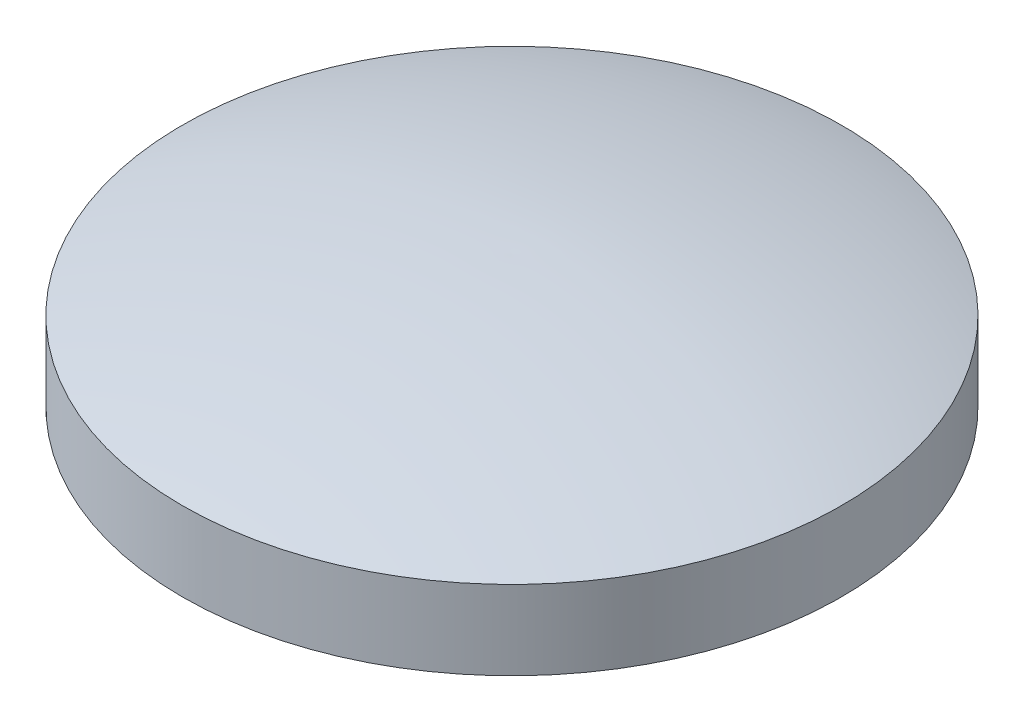
SolidWorks part; units mm, degrees
ref_plane "Front Plane" through (0, 0, 0) normal (0, 0, 1) x (1, 0, 0)
ref_plane "Top Plane" through (0, 0, 0) normal (0, 1, 0) x (1, 0, 0)
ref_plane "Right Plane" through (0, 0, 0) normal (1, 0, 0) x (0, 0, -1)
sketch "Sketch1" plane through (0, 0, 0) normal (0, 1, 0) x (1, 0, 0)
  circle A0 centre (0, 0) radius 12.5
  dimension "D1" = 25
extrude "Boss-Extrude1" add sketch "Sketch1" along normal blind 3
sketch "Sketch2" plane through (0, 0, 0) normal (1, 0, 0) x (0, 0, -1)
  line L0 (0, 3) -> (0, 5.0272)
  line L1 (-12.5, 3) -> (0, 3)
  line L2 (12.5, 3) -> (-12.5, 3) construction
  spline S0 degree 3 poles (-12.5, 3) (-9.2658, 4.1203) (-4.3091, 5.0829) (0, 5.0272) knots 0 0 0 0 0.511837 0.511837 0.511837 0.511837
  dimension "D1" = 5.0272
revolve "Revolve1" add sketch "Sketch2" angle 360 about L0
